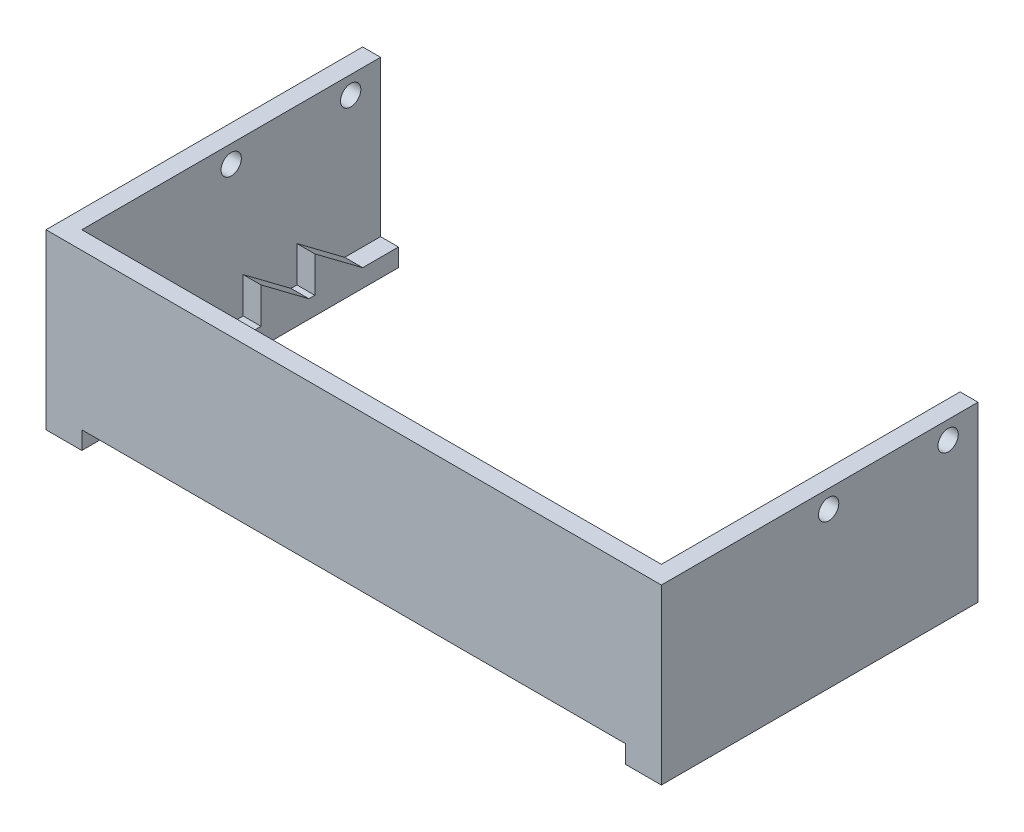
SolidWorks part; units mm, degrees
ref_plane "前视基准面" through (0, 0, 0) normal (0, 0, 1) x (1, 0, 0)
ref_plane "上视基准面" through (0, 0, 0) normal (0, 1, 0) x (1, 0, 0)
ref_plane "右视基准面" through (0, 0, 0) normal (1, 0, 0) x (0, 0, -1)
sketch "草图1" plane through (0, 0, 0) normal (1, 0, 0) x (0, 0, -1)
  line L1 (-25, 13) -> (25, 13)
  line L2 (-25, 13) -> (-25, -13)
  line L3 (-25, -13) -> (25, -13)
  line L4 (25, 13) -> (25, -13)
  line L5 (-25, 13) -> (25, -13) construction
  line L6 (-25, -13) -> (25, 13) construction
  point P0 (0, 0)
  dimension "D1" = 50
  dimension "D2" = 26
extrude "凸台-拉伸1" add sketch "草图1" along normal blind 3
ref_plane "基准面1" through (3, 0, 0) normal (1, 0, 0) x (0, 0, -1)
sketch "草图2" plane through (3, 0, 0) normal (1, 0, 0) x (0, 0, -1)
  line L0 (-25, -13) -> (-17, -13)
  line L1 (-25, -13) -> (25, -13) construction
  line L2 (-17, -13) -> (-17, -7)
  line L3 (-17, -7) -> (-25, -13)
  line L4 (-8, -7) -> (-16, -13)
  line L5 (-16, -13) -> (-8, -13)
  line L6 (-8, -13) -> (-8, -7)
  line L7 (1, -7) -> (-7, -13)
  line L8 (-7, -13) -> (1, -13)
  line L9 (1, -13) -> (1, -7)
  line L10 (10, -7) -> (2, -13)
  line L11 (2, -13) -> (10, -13)
  line L12 (10, -13) -> (10, -7)
  line L13 (19, -7) -> (11, -13)
  line L14 (11, -13) -> (19, -13)
  line L15 (19, -13) -> (19, -7)
  dimension "D1" = 8
  dimension "D2" = 6
  dimension "D3" = 5
extrude "凸台-拉伸2" add sketch "草图2" against normal blind 6
ref_plane "基准面2" through (0, 0, 0) normal (-1, 0, 0) x (0, 0, 1)
sketch "草图4" plane through (3, 0, 0) normal (1, 0, 0) x (0, 0, -1)
  line L0 (-25, -13) -> (25, -13) construction
  line L1 (-25, 13) -> (-28, 13)
  line L2 (-25, 13) -> (-25, -13)
  line L3 (-25, -13) -> (-28, -13)
  line L4 (-28, 13) -> (-28, -13)
  dimension "D1" = 3
sketch "草图5" plane through (0, 0, 0) normal (-1, 0, 0) x (0, 0, 1)
  line L1 (24.95, -12.95) -> (25.05, -12.95)
  line L2 (24.95, -12.95) -> (24.95, -13.05)
  line L3 (24.95, -13.05) -> (25.05, -13.05)
  line L4 (25.05, -12.95) -> (25.05, -13.05)
  line L5 (24.95, -12.95) -> (25.05, -13.05) construction
  line L6 (24.95, -13.05) -> (25.05, -12.95) construction
  point P0 (25, -13)
  dimension "D1" = 0.1
  dimension "D2" = 0.1
extrude "切除-拉伸1" cut sketch "草图5" along normal blind 3
extrude "凸台-拉伸7" add sketch "草图4" against normal blind 103
ref_plane "基准面3" through (0, 0, 25) normal (0, 0, -1) x (-1, 0, 0)
sketch "草图6" plane through (0, 0, 25) normal (0, 0, -1) x (-1, 0, 0)
  line L0 (100, -13) -> (0, -13) construction
  line L1 (100, 13) -> (97, 13)
  line L2 (100, 13) -> (100, -13)
  line L3 (100, -13) -> (97, -13)
  line L4 (97, 13) -> (97, -13)
  dimension "D1" = 3
extrude "凸台-拉伸8" add sketch "草图6" along normal through all
ref_plane "基准面5" through (-97, 0, 0) normal (1, 0, 0) x (0, 0, -1)
sketch "草图7" plane through (-97, 0, 0) normal (1, 0, 0) x (0, 0, -1)
  line L0 (-25, -7) -> (-25, -13)
  line L1 (-25, -14.3) -> (-25, 14.3) construction
  line L2 (-25, -13) -> (-17, -13)
  line L3 (-28, -13) -> (25, -13) construction
  line L4 (-17, -13) -> (-25, -7)
  line L5 (-8, -13) -> (-16, -7)
  line L6 (-16, -13) -> (-8, -13)
  line L7 (-16, -7) -> (-16, -13)
  line L8 (1, -13) -> (-7, -7)
  line L9 (-7, -13) -> (1, -13)
  line L10 (-7, -7) -> (-7, -13)
  line L11 (10, -13) -> (2, -7)
  line L12 (2, -13) -> (10, -13)
  line L13 (2, -7) -> (2, -13)
  line L14 (19, -13) -> (11, -7)
  line L15 (11, -13) -> (19, -13)
  line L16 (11, -7) -> (11, -13)
  dimension "D1" = 8
  dimension "D2" = 6
  dimension "D3" = 5
extrude "凸台-拉伸9" add sketch "草图7" along normal blind 3
ref_plane "基准面6" through (0, -13, 0) normal (0, -1, 0) x (-1, 0, 0)
sketch "草图9" plane through (0, -13, 0) normal (0, -1, 0) x (-1, 0, 0)
  line L0 (94, -7) -> (94, 1) construction
  line L1 (-3, -28) -> (3, -28)
  line L2 (-3, -28) -> (-3, 25)
  line L3 (-3, 25) -> (3, 25)
  line L4 (3, -28) -> (3, 25)
  line L5 (100, -28) -> (94, -28)
  line L6 (100, -28) -> (100, 25)
  line L7 (100, 25) -> (94, 25)
  line L8 (94, -28) -> (94, 25)
  line L9 (-3, 25) -> (0, 25) construction
  line L10 (97, 25) -> (100, 25) construction
extrude "凸台-拉伸12" add sketch "草图9" along normal blind 3
sketch "草图10" plane through (3, 0, 0) normal (1, 0, 0) x (0, 0, -1)
  line L0 (25, 13) -> (-28, 13) construction
  line L1 (25, -16) -> (25, 13) construction
  circle A0 centre (20, 10) radius 1.7
  circle A1 centre (0, 10) radius 1.7
  dimension "D1" = 3.4
  dimension "D2" = 3.4
  dimension "D3" = 3
  dimension "D4" = 3
  dimension "D5" = 5
  dimension "D6" = 20
extrude "切除-拉伸2" cut sketch "草图10" against normal through all
